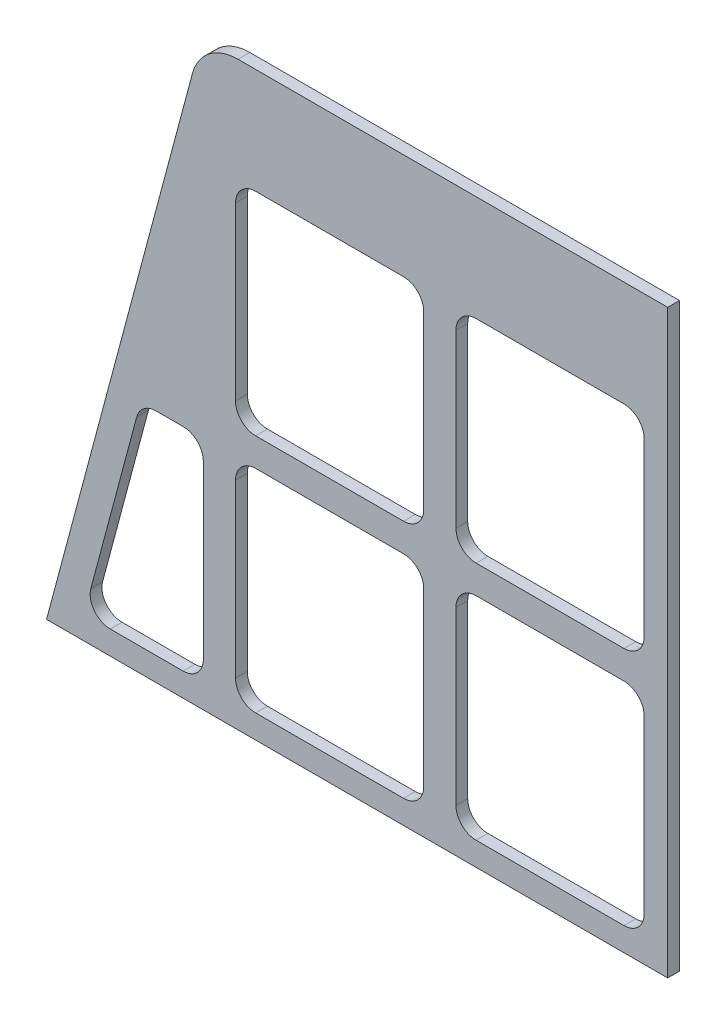
SolidWorks part; units mm, degrees
material "Balsa"
ref_plane "Front Plane" through (0, 0, 0) normal (0, 0, 1) x (1, 0, 0)
ref_plane "Top Plane" through (0, 0, 0) normal (0, 1, 0) x (1, 0, 0)
ref_plane "Right Plane" through (0, 0, 0) normal (1, 0, 0) x (0, 0, -1)
sketch "Sketch1" plane through (0, 0, 0) normal (0, 0, 1) x (1, 0, 0)
  line L0 (0, 0) -> (335.28, 0)
  line L1 (335.28, 0) -> (335.28, 313.5173)
  line L2 (335.28, 313.5173) -> (103.3213, 313.5173)
  line L3 (78.7832, 294.6776) -> (0, 0)
  arc A0 (103.3213, 313.5173) -> (78.7832, 294.6776) centre (103.3213, 288.1173) ccw
  point P8 (83.82, 313.5173)
  point P11 (335.28, 313.5173)
  dimension "D4" = 25.4
  dimension "D1" = 335.28
  dimension "D2" = 313.5173
  dimension "D3" = 251.46
extrude "Boss-Extrude1" add sketch "Sketch1" along normal blind 6.35
sketch "Sketch2" plane through (0, 0, 6.35) normal (0, 0, 1) x (1, 0, 0)
  line L0 (335.28, 0) -> (335.28, 313.5173) construction
  line L1 (311.7054, 12.7) -> (231.8546, 12.7)
  line L2 (322.58, 23.5746) -> (322.58, 116.1254)
  line L3 (311.7054, 127) -> (231.8546, 127)
  line L4 (220.98, 23.5746) -> (220.98, 116.1254)
  line L5 (0, 0) -> (335.28, 0) construction
  line L6 (203.6033, 23.5746) -> (203.6033, 116.1254)
  line L7 (192.7288, 12.7) -> (112.8779, 12.7)
  line L8 (102.0033, 23.5746) -> (102.0033, 116.1254)
  line L9 (192.7288, 127) -> (112.8779, 127)
  line L10 (84.6266, 23.5746) -> (84.6266, 116.1254)
  line L11 (73.7521, 12.7) -> (34.4142, 12.7)
  line L13 (73.7521, 127) -> (59.158, 127)
  line L14 (203.6033, 153.1146) -> (203.6033, 245.6654)
  line L15 (192.7288, 142.24) -> (112.8779, 142.24)
  line L16 (102.0033, 153.1146) -> (102.0033, 245.6654)
  line L17 (192.7288, 256.54) -> (112.8779, 256.54)
  line L18 (84.6266, 153.1146) -> (84.6266, 251.1027)
  line L19 (73.7521, 142.24) -> (69.0472, 142.24)
  line L30 (322.58, 153.1146) -> (322.58, 245.6654)
  line L31 (311.7054, 142.24) -> (231.8546, 142.24)
  line L32 (220.98, 153.1146) -> (220.98, 245.6654)
  line L33 (311.7054, 256.54) -> (231.8546, 256.54)
  line L38 (84.6266, 253.4908) -> (58.5416, 155.9233)
  line L40 (78.7832, 294.6776) -> (0, 0) construction
  line L41 (-16.9734, 12.7) -> (-16.9734, 127) [skipped]
  line L42 (-16.9734, 136.8027) -> (-16.9734, 251.1027) [skipped]
  line L43 (84.6266, 256.54) -> (-16.9734, 256.54) [skipped]
  line L44 (48.6524, 118.9342) -> (23.9086, 26.3833)
  line L45 (84.6266, 271.78) -> (84.6266, 386.08) [skipped]
  line L46 (84.6266, 386.08) -> (-16.9734, 386.08) [skipped]
  line L47 (-16.9734, 271.78) -> (-16.9734, 386.08) [skipped]
  line L48 (84.6266, 271.78) -> (-16.9734, 271.78) [skipped]
  line L49 (203.6033, 271.78) -> (203.6033, 386.08) [skipped]
  line L50 (203.6033, 386.08) -> (102.0033, 386.08) [skipped]
  line L51 (102.0033, 271.78) -> (102.0033, 386.08) [skipped]
  line L52 (203.6033, 271.78) -> (102.0033, 271.78) [skipped]
  line L53 (322.58, 271.78) -> (322.58, 386.08) [skipped]
  line L54 (322.58, 386.08) -> (220.98, 386.08) [skipped]
  line L55 (220.98, 271.78) -> (220.98, 386.08) [skipped]
  line L56 (322.58, 271.78) -> (220.98, 271.78) [skipped]
  arc A0 (69.0472, 142.24) -> (58.5416, 155.9233) centre (69.0472, 153.1146) cw
  arc A1 (84.6266, 153.1146) -> (73.7521, 142.24) centre (73.7521, 153.1146) cw
  arc A2 (84.6266, 23.5746) -> (73.7521, 12.7) centre (73.7521, 23.5746) cw
  arc A3 (34.4142, 12.7) -> (23.9086, 26.3833) centre (34.4142, 23.5746) cw
  arc A4 (59.158, 127) -> (48.6524, 118.9342) centre (59.158, 116.1254) ccw
  arc A5 (84.6266, 116.1254) -> (73.7521, 127) centre (73.7521, 116.1254) ccw
  arc A6 (102.0033, 116.1254) -> (112.8779, 127) centre (112.8779, 116.1254) cw
  arc A7 (112.8779, 12.7) -> (102.0033, 23.5746) centre (112.8779, 23.5746) cw
  arc A8 (203.6033, 23.5746) -> (192.7288, 12.7) centre (192.7288, 23.5746) cw
  arc A9 (203.6033, 116.1254) -> (192.7288, 127) centre (192.7288, 116.1254) ccw
  arc A10 (231.8546, 127) -> (220.98, 116.1254) centre (231.8546, 116.1254) ccw
  arc A11 (231.8546, 12.7) -> (220.98, 23.5746) centre (231.8546, 23.5746) cw
  arc A12 (311.7054, 12.7) -> (322.58, 23.5746) centre (311.7054, 23.5746) ccw
  arc A13 (322.58, 116.1254) -> (311.7054, 127) centre (311.7054, 116.1254) ccw
  arc A14 (322.58, 153.1146) -> (311.7054, 142.24) centre (311.7054, 153.1146) cw
  arc A15 (322.58, 245.6654) -> (311.7054, 256.54) centre (311.7054, 245.6654) ccw
  arc A16 (220.98, 245.6654) -> (231.8546, 256.54) centre (231.8546, 245.6654) cw
  arc A17 (231.8546, 142.24) -> (220.98, 153.1146) centre (231.8546, 153.1146) cw
  arc A18 (112.8779, 142.24) -> (102.0033, 153.1146) centre (112.8779, 153.1146) cw
  arc A19 (203.6033, 153.1146) -> (192.7288, 142.24) centre (192.7288, 153.1146) cw
  arc A20 (203.6033, 245.6654) -> (192.7288, 256.54) centre (192.7288, 245.6654) ccw
  arc A21 (102.0033, 245.6654) -> (112.8779, 256.54) centre (112.8779, 245.6654) cw
  point P33 (50.8088, 127)
  point P83 (220.98, 127)
  point P86 (220.98, 12.7)
  point P91 (322.58, 127)
  dimension "D7" = 10.8746
  dimension "D1" = 114.3
  dimension "D2" = 101.6
  dimension "D3" = 12.7
  dimension "D4" = 12.7
  dimension "D5" = 3
  dimension "D6" = 3
extrude "Cut-Extrude1" cut sketch "Sketch2" along direction (0, 0, 1) on the side against the normal up to surface (6.35 mm away) contours L18 L38 L19 | L14 L17 L16 L15 | L13 L44 L11 L10 | L6 L9 L8 L7 | L4 L1 L2 L3 | L30 L33 L32 L31
